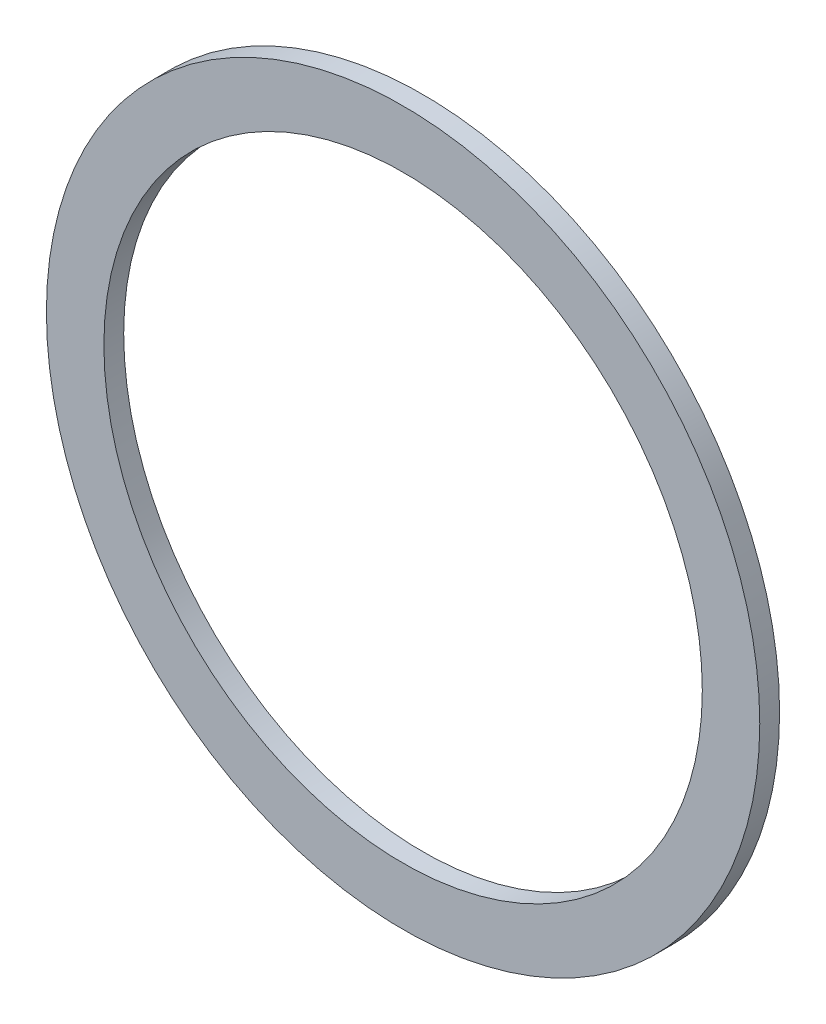
SolidWorks part; units mm, degrees
ref_plane "Front Plane" through (0, 0, 0) normal (1, 0, 0) x (0, 1, 0)
ref_plane "Top Plane" through (0, 0, 0) normal (0, 0, 1) x (0, 1, 0)
ref_plane "Right Plane" through (0, 0, 0) normal (0, 1, 0) x (-1, 0, 0)
sketch "Sketch1" plane through (0, 0, 0) normal (0, 0, 1) x (0, 1, 0)
  circle A0 centre (0, 0) radius 15.1
  circle A1 centre (0, 0) radius 18
  dimension "D1" = 30.2
  dimension "D2" = 36
extrude "Boss-Extrude1" add sketch "Sketch1" along normal blind 1
